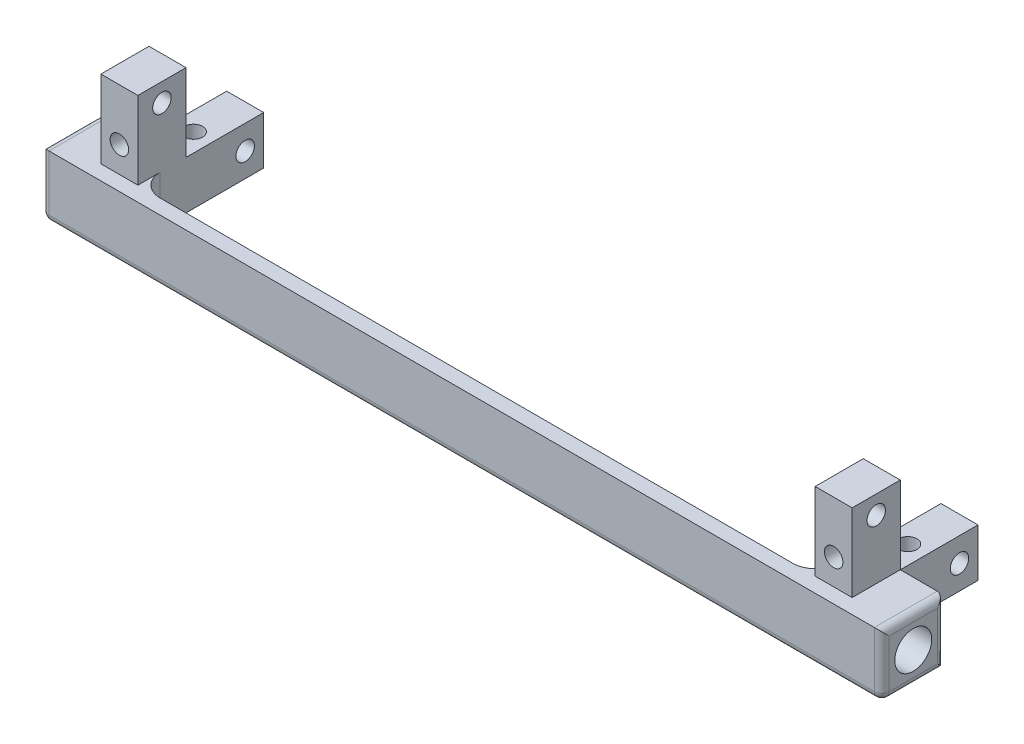
SolidWorks part; units mm, degrees
ref_plane "Front Plane" through (0, 0, 0) normal (0, 0, 1) x (1, 0, 0)
ref_plane "Top Plane" through (0, 0, 0) normal (0, 1, 0) x (1, 0, 0)
ref_plane "Right Plane" through (0, 0, 0) normal (1, 0, 0) x (0, 0, -1)
sketch "Sketch1" plane through (0, 0, 0) normal (0, 0, 1) x (1, 0, 0)
  line L1 (56.75, -4.25) -> (-56.75, -4.25)
  line L2 (56.75, -4.25) -> (56.75, 4.25)
  line L3 (56.75, 4.25) -> (-56.75, 4.25)
  line L4 (-56.75, -4.25) -> (-56.75, 4.25)
  line L5 (56.75, -4.25) -> (-56.75, 4.25) construction
  line L6 (56.75, 4.25) -> (-56.75, -4.25) construction
  point P0 (0, 0)
  dimension "D1" = 113.5
  dimension "D2" = 8.5
extrude "Boss-Extrude1" add sketch "Sketch1" along normal blind 8.5
ref_plane "Plane4" through (50.75, 0, 0) normal (1, 0, 0) x (0, 0, -1)
sketch "Sketch4" plane through (50.75, 0, 0) normal (1, 0, 0) x (0, 0, -1)
  line L0 (0, -2.25) -> (10.5, -2.25)
  line L1 (0, -4.25) -> (0, 4.25) construction
  line L2 (10.5, -2.25) -> (10.5, 14.75)
  line L3 (10.5, 14.75) -> (-6.5, 14.75)
  line L4 (-6.5, 14.75) -> (-6.5, 4.25)
  line L5 (-8.5, 4.25) -> (0, 4.25) construction
  line L6 (-8.5, -4.25) -> (0, -4.25) construction
  line L7 (-8.5, -4.25) -> (-8.5, 4.25) construction
  line L12 (0, -4.25) -> (0, 4.25)
  line L13 (0, 4.25) -> (-8.5, 4.25)
  line L14 (-8.5, 4.25) -> (-8.5, -4.25)
  line L15 (-8.5, -4.25) -> (0, -4.25)
  line L16 (0, -2.25) -> (0, 4.25)
  line L17 (0, 4.25) -> (-6.5, 4.25)
  dimension "D1" = 2
  dimension "D2" = 2
  dimension "D3" = 10.5
  dimension "D4" = 10.5
  dimension "D5" = 0
extrude "Boss-Extrude2" add sketch "Sketch4" against normal blind 5
ref_plane "Plane7" through (-50.75, 0, 0) normal (-1, 0, 0) x (0, 0, 1)
sketch "Sketch12" plane through (-50.75, 0, 0) normal (-1, 0, 0) x (0, 0, 1)
  line L0 (6.5, 4.25) -> (6.5, 14.75)
  line L1 (6.5, 14.75) -> (-10.5, 14.75)
  line L2 (-10.5, 14.75) -> (-10.5, -2.25)
  line L3 (-10.5, -2.25) -> (0, -2.25)
  line L4 (0, -2.25) -> (0, 4.25)
  line L5 (0, 4.25) -> (6.5, 4.25)
extrude "Boss-Extrude3" add sketch "Sketch12" against normal blind 5
sketch "Sketch13" plane through (0, 4.25, 0) normal (0, 1, 0) x (1, 0, 0)
  line L1 (-45.75, 0) -> (45.75, 0)
  line L2 (-45.75, 0) -> (-45.75, -6.5)
  line L3 (-45.75, -6.5) -> (45.75, -6.5)
  line L4 (45.75, 0) -> (45.75, -6.5)
extrude "Cut-Extrude1" cut sketch "Sketch13" against normal blind 6.5
hole_wizard "M3x0.5 Tapped Hole1" positions "Sketch16" profile "Sketch15" tap size "M3x0.5" standard "Ansi Metric"
sketch "Sketch16" plane through (0, 0, 6.5) normal (0, 0, 1) x (1, 0, 0)
  line L0 (-45.75, 4.25) -> (-50.75, 4.25) construction
  line L3 (-45.75, 4.25) -> (-45.75, 14.75) construction
  point P0 (-48.25, 7.75)
  dimension "D1" = 3.5
  dimension "D2" = 2.5
sketch "Sketch15" plane through (-48.25, 7.75, 6.5) normal (1, 0, 0) x (0, -1, 0)
  line L0 (0, 0) -> (0, 8.2511)
  line L1 (0, 8.2511) -> (1.25, 7.5)
  line L2 (1.25, 7.5) -> (1.25, 0)
  line L5 (1.25, 0) -> (0, 0)
  line L10 (0, 8.2511) -> (-1.25, 7.5) construction
  line L11 (0, -6.35) -> (0, 107.95) construction
  dimension "Tap Drill Dia." = 2.5
  dimension "Tap Drill Depth" = 7.5
  dimension "Drill Angle" = 118
cosmetic thread "Hole Thread1" parameters "D1"=6, "D2"=3
hole_wizard "M3x0.5 Tapped Hole2" positions "Sketch18" profile "Sketch19" tap size "M3x0.5" standard "Ansi Metric"
sketch "Sketch18" plane through (-50.75, 0, 0) normal (-1, 0, 0) x (0, 0, 1)
  line L0 (6.5, 4.25) -> (6.5, 14.75) construction
  line L1 (8.5, 4.25) -> (0, 4.25) construction
  point P0 (3.25, 12.25)
  dimension "D1" = 3.25
  dimension "D2" = 8
sketch "Sketch19" plane through (-50.75, 12.25, 3.25) normal (0, 1, 0) x (0, 0, 1)
  line L0 (0, 0) -> (0, 5)
  line L1 (0, 5) -> (1.25, 5)
  line L2 (1.25, 5) -> (1.25, 0)
  line L5 (1.25, 0) -> (0, 0)
  line L11 (0, -6.35) -> (0, 107.95) construction
  dimension "Thru Tap Drill Dia." = 2.5
  dimension "Thru Tap Drill Depth" = 5
cosmetic thread "Hole Thread9" parameters "D2"=3
hole_wizard "M3x0.5 Tapped Hole3" positions "Sketch21" profile "Sketch20" tap size "M3x0.5" standard "Ansi Metric"
sketch "Sketch21" plane through (-50.75, 0, 0) normal (-1, 0, 0) x (0, 0, 1)
  line L0 (0, 4.25) -> (0, -4.25) construction
  line L1 (-10.5, -2.25) -> (0, -2.25) construction
  point P0 (-8, 1)
  dimension "D1" = 8
  dimension "D2" = 3.25
cosmetic thread "Hole Thread3" parameters "D2"=3
sketch "Sketch20" plane through (-50.75, 1, -8) normal (0, 1, 0) x (0, 0, 1)
  line L0 (0, 0) -> (0, 5)
  line L1 (0, 5) -> (1.25, 5)
  line L2 (1.25, 5) -> (1.25, 0)
  line L5 (1.25, 0) -> (0, 0)
  line L11 (0, -6.35) -> (0, 107.95) construction
  dimension "Thru Tap Drill Dia." = 2.5
  dimension "Thru Tap Drill Depth" = 5
hole_wizard "M3x0.5 Tapped Hole4" positions "Sketch23" profile "Sketch22" tap size "M3x0.5" standard "Ansi Metric"
sketch "Sketch23" plane through (0, -2.25, 0) normal (0, -1, 0) x (1, 0, 0)
  line L1 (-45.75, -10.5) -> (-45.75, 0) construction
  line L2 (-56.75, 0) -> (56.75, 0) construction
  point P0 (-48.25, -3.5)
  dimension "D1" = 2.5
  dimension "D2" = 3.5
sketch "Sketch22" plane through (-48.25, -2.25, -3.5) normal (1, 0, 0) x (0, 0, -1)
  line L0 (0, 0) -> (0, 8.2511)
  line L1 (0, 8.2511) -> (1.25, 7.5)
  line L2 (1.25, 7.5) -> (1.25, 0)
  line L5 (1.25, 0) -> (0, 0)
  line L10 (0, 8.2511) -> (-1.25, 7.5) construction
  line L11 (0, -6.35) -> (0, 107.95) construction
  dimension "Tap Drill Dia." = 2.5
  dimension "Tap Drill Depth" = 7.5
  dimension "Drill Angle" = 118
cosmetic thread "Hole Thread5" parameters "D1"=6, "D2"=3
fillet "Fillet1" radius 1 1 edges at (0, -4.25, 8.5)
fillet "Fillet2" radius 1 5 edges at (-56.75, -4.25, 3.75) (-56.75, -3.9571, 8.2071) (-56.75, 4.25, 4.25) (-56.75, 0, 0) (-56.75, 0.5, 8.5)
fillet "Fillet3" radius 1 5 edges at (56.75, -4.25, 3.75) (56.75, -3.9571, 8.2071) (56.75, 0, 0) (56.75, 0.5, 8.5) (56.75, 4.25, 4.25)
fillet "Fillet4" radius 3 2 edges at (45.75, 1, 6.5) (-45.75, 1, 6.5)
hole_wizard "M3x0.5 Tapped Hole5" positions "Sketch28" profile "Sketch27" tap size "M3x0.5" standard "Ansi Metric"
sketch "Sketch28" plane through (0, 0, 6.5) normal (0, 0, 1) x (1, 0, 0)
  line L0 (45.75, 14.75) -> (45.75, 4.25) construction
  line L3 (45.75, 4.25) -> (50.75, 4.25) construction
  point P0 (48.25, 7.75)
  dimension "D1" = 2.5
  dimension "D2" = 3.5
sketch "Sketch27" plane through (48.25, 7.75, 6.5) normal (1, 0, 0) x (0, -1, 0)
  line L0 (0, 0) -> (0, 8.2511)
  line L1 (0, 8.2511) -> (1.25, 7.5)
  line L2 (1.25, 7.5) -> (1.25, 0)
  line L5 (1.25, 0) -> (0, 0)
  line L10 (0, 8.2511) -> (-1.25, 7.5) construction
  line L11 (0, -6.35) -> (0, 107.95) construction
  dimension "Tap Drill Dia." = 2.5
  dimension "Tap Drill Depth" = 7.5
  dimension "Drill Angle" = 118
cosmetic thread "Hole Thread6" parameters "D1"=6, "D2"=3
hole_wizard "M3x0.5 Tapped Hole6" positions "Sketch30" profile "Sketch29" tap size "M3x0.5" standard "Ansi Metric"
sketch "Sketch30" plane through (0, -2.25, 0) normal (0, -1, 0) x (1, 0, 0)
  line L0 (45.75, 0) -> (50.75, 0) construction
  line L1 (45.75, 0) -> (45.75, -10.5) construction
  point P0 (48.25, -3.5)
  dimension "D1" = 3.5
  dimension "D2" = 2.5
sketch "Sketch29" plane through (48.25, -2.25, -3.5) normal (1, 0, 0) x (0, 0, -1)
  line L0 (0, 0) -> (0, 8.2511)
  line L1 (0, 8.2511) -> (1.25, 7.5)
  line L2 (1.25, 7.5) -> (1.25, 0)
  line L5 (1.25, 0) -> (0, 0)
  line L10 (0, 8.2511) -> (-1.25, 7.5) construction
  line L11 (0, -6.35) -> (0, 107.95) construction
  dimension "Tap Drill Dia." = 2.5
  dimension "Tap Drill Depth" = 7.5
  dimension "Drill Angle" = 118
cosmetic thread "Hole Thread7" parameters "D1"=6, "D2"=3
hole_wizard "M3x0.5 Tapped Hole7" positions "Sketch32" profile "Sketch31" tap size "M3x0.5" standard "Ansi Metric"
sketch "Sketch32" plane through (50.75, 0, 0) normal (1, 0, 0) x (0, 0, -1)
  line L0 (0, 4.25) -> (0, -2.25) construction
  line L1 (0, -2.25) -> (10.5, -2.25) construction
  point P0 (8, 1)
  dimension "D1" = 8
  dimension "D2" = 3.25
sketch "Sketch31" plane through (50.75, 1, -8) normal (0, 1, 0) x (0, 0, -1)
  line L0 (0, 0) -> (0, 8.2511)
  line L1 (0, 8.2511) -> (1.25, 7.5)
  line L2 (1.25, 7.5) -> (1.25, 0)
  line L5 (1.25, 0) -> (0, 0)
  line L10 (0, 8.2511) -> (-1.25, 7.5) construction
  line L11 (0, -6.35) -> (0, 107.95) construction
  dimension "Tap Drill Dia." = 2.5
  dimension "Tap Drill Depth" = 7.5
  dimension "Drill Angle" = 118
cosmetic thread "Hole Thread8" parameters "D1"=5, "D2"=3
hole_wizard "M3x0.5 Tapped Hole9" positions "Sketch36" profile "Sketch35" tap size "M3x0.5" standard "Ansi Metric"
sketch "Sketch36" plane through (50.75, 0, 0) normal (1, 0, 0) x (0, 0, -1)
  line L0 (-6.5, 4.25) -> (0, 4.25) construction
  line L1 (-6.5, 14.75) -> (-6.5, 4.25) construction
  point P0 (-3.25, 12.25)
  dimension "D1" = 8
  dimension "D2" = 3.25
sketch "Sketch35" plane through (50.75, 12.25, 3.25) normal (0, 1, 0) x (0, 0, -1)
  line L0 (0, 0) -> (0, 8.2511)
  line L1 (0, 8.2511) -> (1.25, 7.5)
  line L2 (1.25, 7.5) -> (1.25, 0)
  line L5 (1.25, 0) -> (0, 0)
  line L10 (0, 8.2511) -> (-1.25, 7.5) construction
  line L11 (0, -6.35) -> (0, 107.95) construction
  dimension "Tap Drill Dia." = 2.5
  dimension "Tap Drill Depth" = 7.5
  dimension "Drill Angle" = 118
cosmetic thread "Hole Thread11" parameters "D1"=5, "D2"=3
sketch "Sketch43" plane through (-50.75, 0, 0) normal (-1, 0, 0) x (0, 0, 1)
  line L1 (6.5, 14.75) -> (-10.5, 14.75) construction
  line L2 (-10.5, 14.75) -> (-10.5, -2.25) construction
  line L3 (-10.5, 4.25) -> (-10.5, 14.75)
  line L4 (-10.5, 14.75) -> (0, 14.75)
  line L5 (-10.5, 4.25) -> (0, 4.25)
  line L6 (0, 4.25) -> (0, 14.75)
  point P6 (-5.25, 4.25)
  point P9 (-5.25, 9.5)
  point P10 (0, 9.5)
extrude "Cut-Extrude3" cut sketch "Sketch43" against normal through all
sketch "Sketch44" plane through (56.75, 0, 0) normal (1, 0, 0) x (0, 0, -1)
  line L0 (-8.5, -3.25) -> (-8.5, 4.25) construction
  line L1 (-8.5, 4.25) -> (0, 4.25) construction
  circle A0 centre (-4.25, 0) radius 2.5
  dimension "D1" = 5
  dimension "D2" = 4.25
  dimension "D3" = 4.25
extrude "Cut-Extrude4" cut sketch "Sketch44" against normal blind 10
sketch "Sketch45" plane through (46.75, 0, 0) normal (1, 0, 0) x (0, 0, -1)
  circle A0 centre (-4.25, 0) radius 1.25
  dimension "D1" = 2.5
extrude "Cut-Extrude5" cut sketch "Sketch45" against normal up to next
hole_wizard "M6 Tapped Hole1" positions "Sketch49" profile "Sketch48" tap size "M6x1.0" standard "Ansi Metric"
sketch "Sketch49" plane through (56.75, 0, 0) normal (1, 0, 0) x (0, 0, -1)
  line L0 (-8.5, 4.25) -> (0, 4.25) construction
  line L1 (-8.5, -3.25) -> (-8.5, 4.25) construction
  point P0 (-4.25, 0)
  dimension "D1" = 4.25
  dimension "D2" = 4.25
sketch "Sketch48" plane through (56.75, 0, 4.25) normal (0, 1, 0) x (0, 0, -1)
  line L0 (0, 0) -> (0, 4.5522)
  line L1 (0, 4.5522) -> (2.5, 3.05)
  line L2 (2.5, 3.05) -> (2.5, 0)
  line L5 (2.5, 0) -> (0, 0)
  line L10 (0, 4.5522) -> (-2.5, 3.05) construction
  line L11 (0, -6.35) -> (0, 107.95) construction
  dimension "Tap Drill Dia." = 5
  dimension "Tap Drill Depth" = 3.05
  dimension "Drill Angle" = 118
